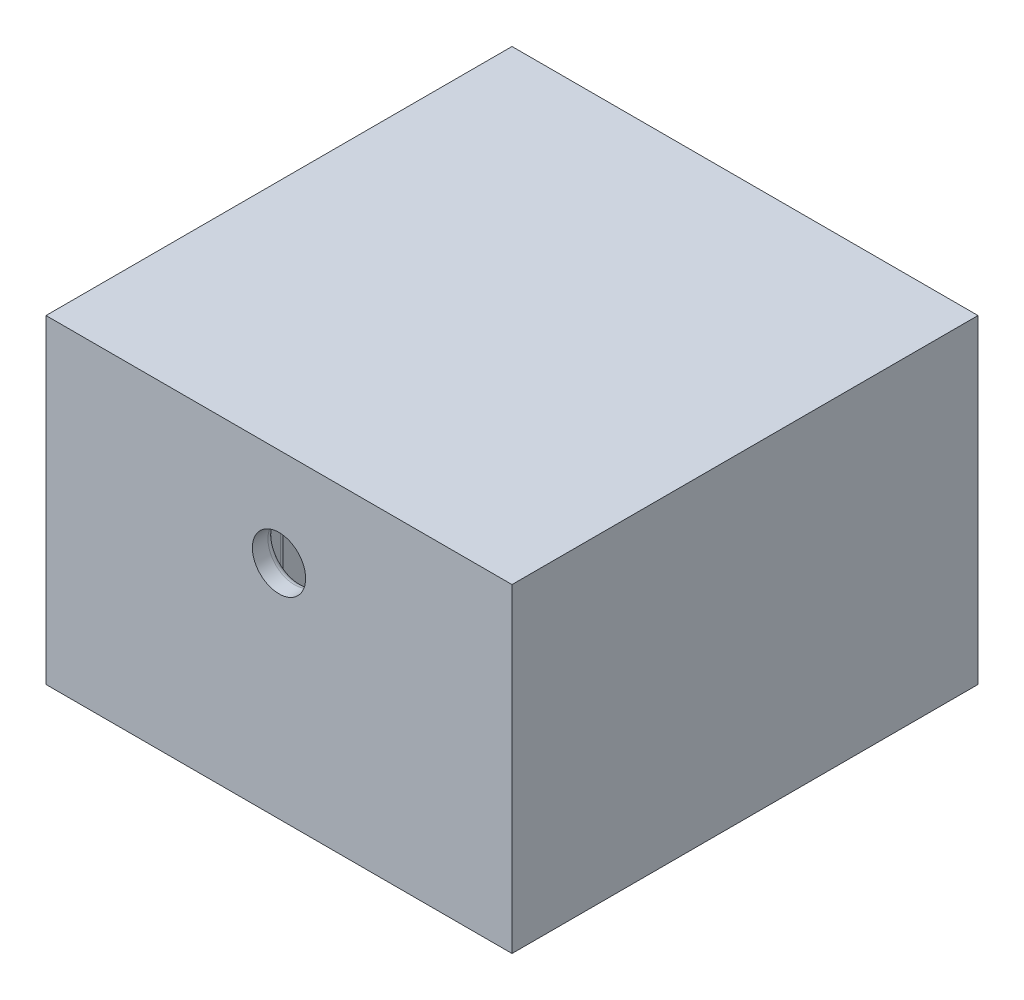
SolidWorks part; units mm, degrees
ref_plane "Front Plane" through (0, 0, 0) normal (0, 0, 1) x (1, 0, 0)
ref_plane "Top Plane" through (0, 0, 0) normal (0, 1, 0) x (1, 0, 0)
ref_plane "Right Plane" through (0, 0, 0) normal (1, 0, 0) x (0, 0, -1)
sketch "Sketch1" plane through (0, 0, 0) normal (0, 1, 0) x (1, 0, 0)
  line L0 (22.315, 0) -> (22.315, -63.32) construction
  line L1 (1, 0) -> (43.63, 0)
  line L2 (0, -1) -> (0, -62.32)
  line L3 (1, -63.32) -> (43.63, -63.32)
  line L4 (44.63, -1) -> (44.63, -62.32)
  line L5 (22.315, -63.32) -> (22.315, -31.66) construction
  line L6 (22.315, -31.66) -> (44.63, -31.66) construction
  line L7 (44.63, -31.66) -> (0, -31.66) construction
  line L9 (-12.685, 3.34) -> (57.315, 3.34)
  line L10 (-12.685, 3.34) -> (-12.685, -66.66)
  line L11 (-12.685, -66.66) -> (57.315, -66.66)
  line L12 (57.315, 3.34) -> (57.315, -66.66)
  arc A0 (0, -62.32) -> (1, -63.32) centre (1, -62.32) ccw
  arc A1 (43.63, -63.32) -> (44.63, -62.32) centre (43.63, -62.32) ccw
  arc A2 (43.63, 0) -> (44.63, -1) centre (43.63, -1) cw
  arc A3 (1, 0) -> (0, -1) centre (1, -1) ccw
  point P13 (0, 0)
  dimension "D3" = 1
  dimension "D1" = 63.32
  dimension "D2" = 44.63
  dimension "D4" = 35
  dimension "D5" = 35
  dimension "D6" = 35
  dimension "D7" = 35
extrude "Boss-Extrude1" add sketch "Sketch1" along normal blind 42
sketch "Sketch2" plane through (0, 42, 0) normal (0, 1, 0) x (1, 0, 0)
  line L1 (-12.685, 3.34) -> (57.315, 3.34)
  line L2 (-12.685, 3.34) -> (-12.685, -66.66)
  line L3 (-12.685, -66.66) -> (57.315, -66.66)
  line L4 (57.315, 3.34) -> (57.315, -66.66)
extrude "Boss-Extrude2" add sketch "Sketch2" along normal blind 6
sketch "Sketch3" plane through (0, 0, 66.66) normal (0, 0, 1) x (1, 0, 0)
  line L0 (-12.685, 24) -> (57.315, 24) construction
  line L1 (-12.685, 48) -> (-12.685, 0) construction
  line L2 (57.315, 48) -> (57.315, 0) construction
  line L3 (57.315, 24) -> (22.315, 24) construction
  line L4 (22.315, 24) -> (22.315, 0) construction
  line L5 (-12.685, 0) -> (57.315, 0) construction
  line L6 (22.315, 0) -> (22.315, 48) construction
  line L7 (-12.685, 48) -> (57.315, 48) construction
  circle A0 centre (22.315, 33.2894) radius 4
extrude "Cut-Extrude1" cut sketch "Sketch3" against normal blind 74
sketch "Sketch6" plane through (0, 42, 0) normal (0, -1, 0) x (-1, 0, 0)
  line L1 (0, -63.32) -> (-10.0781, -63.32)
  line L2 (0, -63.32) -> (0, -53.1996)
  line L3 (0, -53.1996) -> (-10.0781, -53.1996)
  line L4 (-10.0781, -63.32) -> (-10.0781, -53.1996)
  line L5 (-44.63, -63.32) -> (-34.4922, -63.32)
  line L6 (-44.63, -63.32) -> (-44.63, -53.1996)
  line L7 (-44.63, -53.1996) -> (-34.4922, -53.1996)
  line L8 (-34.4922, -63.32) -> (-34.4922, -53.1996)
  line L9 (-44.63, 0) -> (-34.4922, 0)
  line L10 (-44.63, 0) -> (-44.63, -10.394)
  line L11 (-44.63, -10.394) -> (-34.4922, -10.394)
  line L12 (-34.4922, 0) -> (-34.4922, -10.394)
  line L13 (0, 0) -> (-10.0781, 0)
  line L14 (0, 0) -> (0, -10.394)
  line L15 (0, -10.394) -> (-10.0781, -10.394)
  line L16 (-10.0781, 0) -> (-10.0781, -10.394)
extrude "Boss-Extrude4" add sketch "Sketch6" along normal blind 28
fillet "Fillet1" radius 1 4 edges at (10.0781, 28, 53.1996) (10.0781, 28, 10.394) (34.4922, 28, 10.394) (34.4922, 28, 53.1996)
sketch "Sketch4" plane through (0, 42, 0) normal (0, -1, 0) x (1, 0, 0)
  line L0 (0, 62.32) -> (1, 62.32) construction
  line L1 (1, 62.32) -> (1, 63.32) construction
  line L2 (43.63, 63.32) -> (43.63, 62.32) construction
  line L3 (43.63, 62.32) -> (44.63, 62.32) construction
  line L4 (43.63, 0) -> (43.63, 1) construction
  line L5 (43.63, 1) -> (44.63, 1) construction
  line L6 (0, 1) -> (1, 1) construction
  line L7 (1, 1) -> (1, 0) construction
  line L8 (0.2929, 63.0271) -> (5.7036, 57.6164) construction
  line L9 (44.3371, 63.0271) -> (38.9264, 57.6164) construction
  line L10 (44.3371, 0.2929) -> (38.9264, 5.7036) construction
  line L11 (0.2929, 0.2929) -> (5.7036, 5.7036) construction
  arc A0 (1, 63.32) -> (0, 62.32) centre (1, 62.32) ccw construction
  arc A1 (44.63, 62.32) -> (43.63, 63.32) centre (43.63, 62.32) ccw construction
  arc A2 (43.63, 0) -> (44.63, 1) centre (43.63, 1) ccw construction
  arc A3 (0, 1) -> (1, 0) centre (1, 1) ccw construction
  circle A4 centre (5.7036, 5.7036) radius 3
  circle A5 centre (5.7036, 5.7036) radius 4.2
  circle A6 centre (38.9264, 5.7036) radius 3
  circle A7 centre (38.9264, 5.7036) radius 4.2
  circle A8 centre (38.9264, 57.6164) radius 3
  circle A9 centre (38.9264, 57.6164) radius 4.2
  circle A10 centre (5.7036, 57.6164) radius 3
  circle A11 centre (5.7036, 57.6164) radius 4.2
extrude "Boss-Extrude3" add sketch "Sketch4" along normal blind 32
sketch "Sketch8" plane through (0, 14, 0) normal (0, -1, 0) x (-1, 0, 0)
  circle A0 centre (-5.7036, -57.6164) radius 3
  circle A1 centre (-38.9264, -57.6164) radius 3
  circle A2 centre (-38.9264, -5.7036) radius 3
  circle A3 centre (-5.7036, -5.7036) radius 3
extrude "Cut-Extrude2" cut sketch "Sketch8" against normal blind 28
fillet "Fillet2" radius 1 2 edges at (26.315, 33.2894, 0) (18.315, 33.2894, 63.32)
